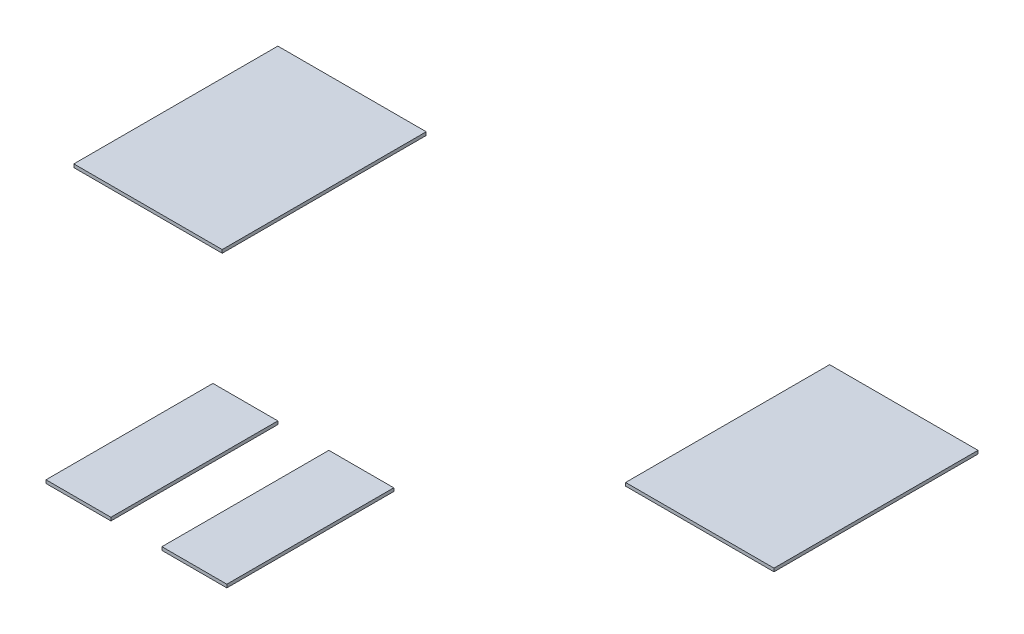
SolidWorks part; units mm, degrees
material "Copper"
ref_plane "Front Plane" through (0, 0, 0) normal (0, 0, 1) x (1, 0, 0)
ref_plane "Top Plane" through (0, 0, 0) normal (0, 1, 0) x (1, 0, 0)
ref_plane "Right Plane" through (0, 0, 0) normal (1, 0, 0) x (0, 0, -1)
sketch "Sketch1" plane through (0, 0, 0) normal (0, 1, 0) x (1, 0, 0)
  line L0 (0, 0) -> (0, 9.6533) construction
  line L1 (-0.275, 0) -> (-0.975, 0)
  line L2 (0.275, 0) -> (0.975, 0)
  line L3 (0.275, 0) -> (0.275, 1.8)
  line L4 (0.275, 1.8) -> (0.975, 1.8)
  line L5 (0, 0) -> (7.1604, 0) construction
  line L6 (0.975, 0) -> (0.975, 1.8)
  line L7 (2.175, 5.3) -> (3.775, 5.3)
  line L8 (2.175, 5.3) -> (2.175, 3.1)
  line L9 (2.175, 3.1) -> (3.775, 3.1)
  line L10 (3.775, 5.3) -> (3.775, 3.1)
  line L11 (-0.275, 0) -> (-0.275, 1.8)
  line L12 (-0.975, 0) -> (-0.975, 1.8)
  line L13 (-0.275, 1.8) -> (-0.975, 1.8)
  line L14 (-2.175, 3.1) -> (-3.775, 3.1)
  line L15 (-3.775, 5.3) -> (-3.775, 3.1)
  line L16 (-2.175, 5.3) -> (-3.775, 5.3)
  line L17 (-2.175, 5.3) -> (-2.175, 3.1)
  point P12 (2.175, 4.2)
  dimension "D1" = 0.7
  dimension "D2" = 1.8
  dimension "D3" = 0.275
  dimension "D4" = 1.6
  dimension "D5" = 2.2
  dimension "D6" = 2.175
  dimension "D7" = 2.4
extrude "Boss-Extrude1" add sketch "Sketch1" along normal blind 0.035
